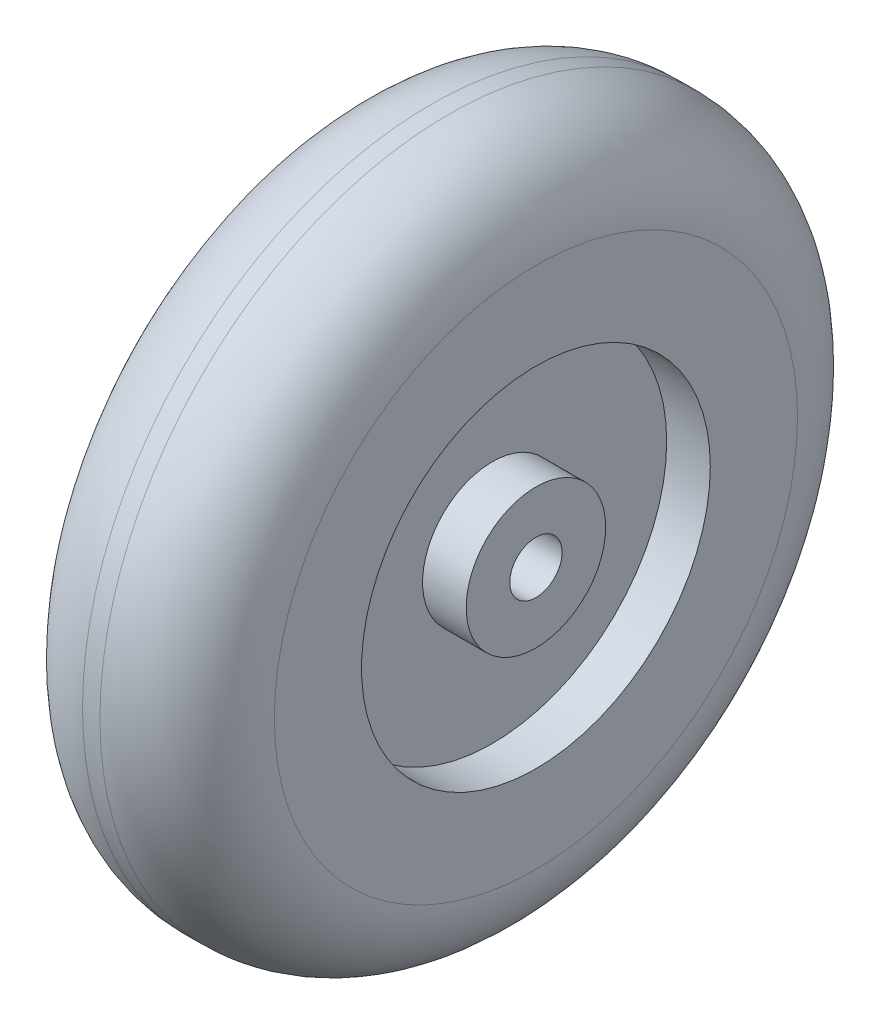
SolidWorks part; units mm, degrees
ref_plane "Front Plane" through (0, 0, 0) normal (0, 0, 1) x (1, 0, 0)
ref_plane "Top Plane" through (0, 0, 0) normal (0, 1, 0) x (1, 0, 0)
ref_plane "Right Plane" through (0, 0, 0) normal (1, 0, 0) x (0, 0, -1)
sketch "Sketch2" plane through (0, 0, 0) normal (1, 0, 0) x (0, 0, -1)
  circle A0 centre (0, 0) radius 20
  circle A1 centre (0, 0) radius 1.5
extrude "Boss-Extrude1" add sketch "Sketch2" along normal mid plane 11
fillet "Fillet1" radius 5 2 edges at (-5.5, 0, -20) (5.5, 0, -20)
sketch "Sketch3" plane through (5.5, 0, 0) normal (1, 0, 0) x (0, 0, -1)
  circle A0 centre (0, 0) radius 4
  circle A1 centre (0, 0) radius 10
  dimension "D1" = 20
  dimension "D2" = 8
extrude "Cut-Extrude1" cut sketch "Sketch3" against normal blind 2.5
sketch "Sketch4" plane through (-5.5, 0, 0) normal (-1, 0, 0) x (0, 0, 1)
  circle A1 centre (0, 0) radius 10
  circle A2 centre (0, 0) radius 10
  circle A3 centre (0, 0) radius 4
  circle A4 centre (0, 0) radius 4
  dimension "D1" = 0
  dimension "D2" = 0
extrude "Cut-Extrude2" cut sketch "Sketch4" against normal blind 2.5
